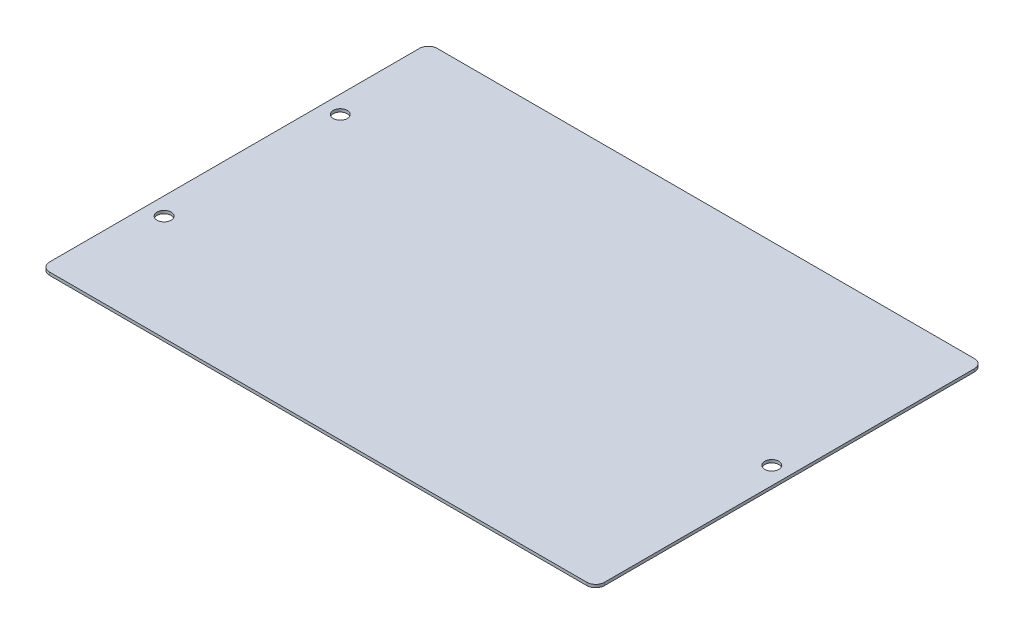
SolidWorks part; units mm, degrees
material "Stainless Steel (ferritic)"
ref_plane "Front Plane" through (0, 0, 0) normal (0, 0, 1) x (1, 0, 0)
ref_plane "Top Plane" through (0, 0, 0) normal (0, 1, 0) x (1, 0, 0)
ref_plane "Right Plane" through (0, 0, 0) normal (1, 0, 0) x (0, 0, -1)
sketch "Sketch1" plane through (0, 0, 0) normal (0, 1, 0) x (1, 0, 0)
  line L1 (-94.5, 66) -> (94.5, 66)
  line L2 (-94.5, 66) -> (-94.5, -66)
  line L3 (-94.5, -66) -> (94.5, -66)
  line L4 (94.5, 66) -> (94.5, -66)
  line L5 (-94.5, 66) -> (94.5, -66) construction
  line L6 (-94.5, -66) -> (94.5, 66) construction
  point P0 (0, 0)
  dimension "D1" = 189
  dimension "D2" = 132
extrude "Boss-Extrude1" add sketch "Sketch1" along normal blind 1
sketch "Sketch2" plane through (0, 1, 0) normal (0, 1, 0) x (1, 0, 0)
  line L0 (94.5, -66) -> (94.5, 66) construction
  line L1 (79.5, -51) -> (-79.5, -51) construction
  line L2 (79.5, -51) -> (79.5, 51) construction
  line L3 (79.5, 51) -> (-79.5, 51) construction
  line L4 (-79.5, -51) -> (-79.5, 51) construction
  line L5 (79.5, -51) -> (-79.5, 51) construction
  line L6 (79.5, 51) -> (-79.5, -51) construction
  line L7 (-94.5, -66) -> (94.5, -66) construction
  line L8 (-94.5, 66) -> (-94.5, -66) construction
  line L9 (94.5, 66) -> (-94.5, 66) construction
  point P0 (0, 0)
  dimension "D1" = 15
  dimension "D2" = 15
  dimension "D3" = 15
  dimension "D4" = 15
sketch "Sketch3" plane through (0, 1, 0) normal (0, 1, 0) x (1, 0, 0)
  line L0 (94.5, -66) -> (94.5, 66) construction
  line L1 (88.5, 0) -> (-94.5, 0) construction
  line L2 (88.5, 0) -> (94.5, 0) construction
  line L3 (-94.5, 66) -> (-94.5, -66) construction
  line L4 (-94.5, 66) -> (-94.5, -66) construction
  line L7 (88.5, 2.4) -> (88.5, -2.4) construction
  circle A4 centre (88.5, 0) radius 2.4
  circle A5 centre (-88.5, -30) radius 2.4
  circle A6 centre (-88.5, 30) radius 2.4
  dimension "D1" = 4.8
  dimension "D4" = 60
  dimension "D2" = 6
  dimension "D3" = 6
extrude "Cut-Extrude1" cut sketch "Sketch3" against normal through all
fillet "Fillet1" radius 3 4 edges at (94.5, 0.5, 66) (94.5, 0.5, -66) (-94.5, 0.5, 66) (-94.5, 0.5, -66)
